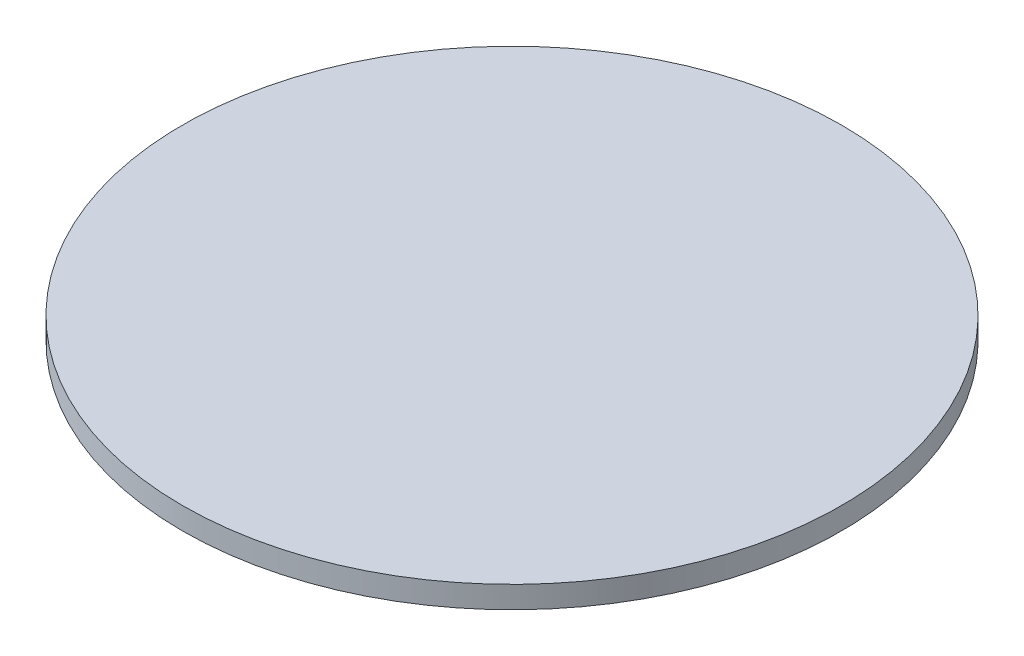
SolidWorks part; units mm, degrees
material "6061 Alloy"
ref_plane "Front Plane" through (0, 0, 0) normal (0, 0, 1) x (1, 0, 0)
ref_plane "Top Plane" through (0, 0, 0) normal (0, 1, 0) x (1, 0, 0)
ref_plane "Right Plane" through (0, 0, 0) normal (1, 0, 0) x (0, 0, -1)
sketch "Sketch1" plane through (0, 0, 0) normal (0, 1, 0) x (1, 0, 0)
  circle A0 centre (0, 0) radius 95.123
  dimension "D1" = 190.246
extrude "Boss-Extrude1" add sketch "Sketch1" along normal blind 6.35
